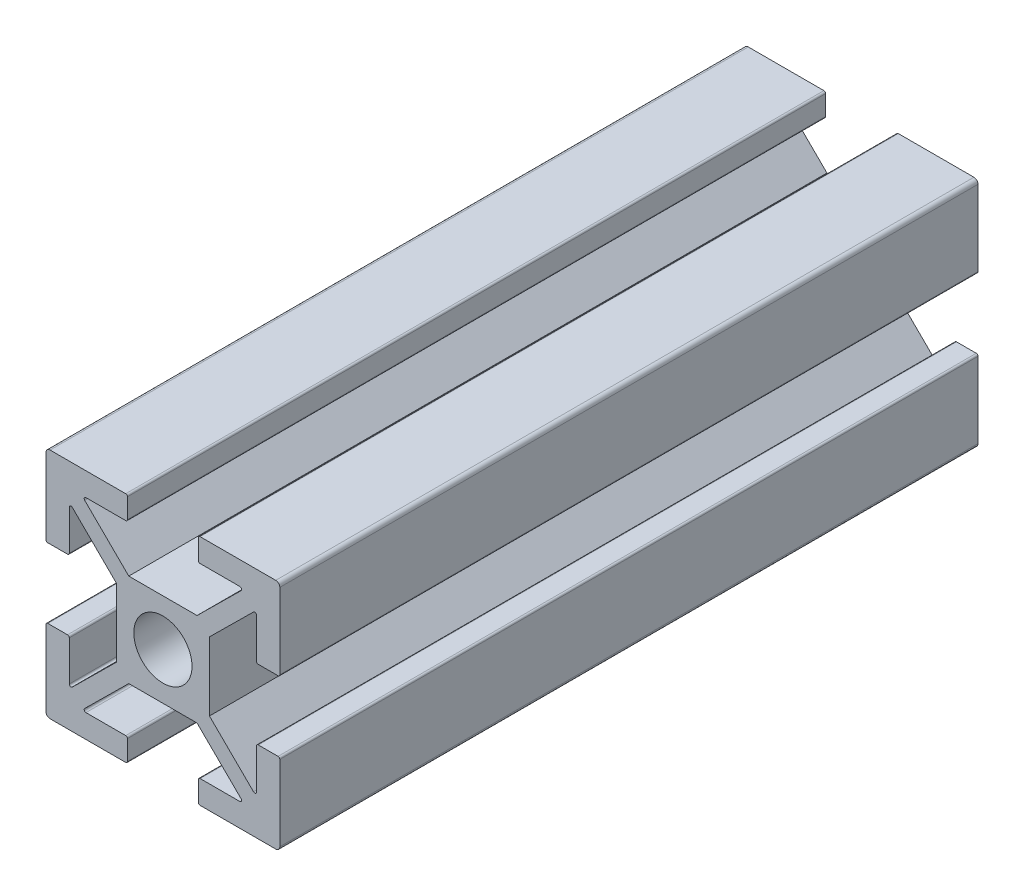
SolidWorks part; units mm, degrees
ref_plane "Front Plane" through (0, 0, 0) normal (0, 0, 1) x (1, 0, 0)
ref_plane "Top Plane" through (0, 0, 0) normal (0, 1, 0) x (1, 0, 0)
ref_plane "Right Plane" through (0, 0, 0) normal (1, 0, 0) x (0, 0, -1)
sketch "Sketch1" plane through (0, 0, 0) normal (0, 0, 1) x (1, 0, 0)
  line L0 (-31.3764, -0.0618) -> (-29.6764, -0.0618)
  line L1 (-24.6764, 6.9382) -> (-31.1764, 6.9382)
  line L2 (-31.5264, 0.0882) -> (-31.5264, 6.5882)
  line L3 (-18.5469, 0.9382) -> (-24.4133, 0.9382)
  line L4 (-25.4801, -6.0072) -> (-25.4801, -0.1164)
  line L5 (-29.5264, 0.0882) -> (-29.5264, 3.5244)
  line L6 (-28.0945, 4.9382) -> (-24.6764, 4.9382)
  line L7 (-24.5264, 5.0882) -> (-24.5264, 6.7882)
  line L8 (-29.5264, 4.9382) -> (-25.4801, 0.9382) construction
  line L9 (-29.271, 3.631) -> (-25.4801, -0.1164)
  line L10 (-28.1999, 4.6815) -> (-24.4133, 0.9382)
  line L11 (-13.4338, 4.9382) -> (-17.4801, 0.9382) construction
  line L12 (-21.4801, -3.0618) -> (-21.4801, 8.6268) construction
  line L13 (-21.4801, -3.0618) -> (-36.4642, -3.0618) construction
  line L14 (-14.7603, 4.6815) -> (-18.5469, 0.9382)
  line L15 (-13.6893, 3.631) -> (-17.4801, -0.1164)
  line L16 (-18.4338, 5.0882) -> (-18.4338, 6.7882)
  line L17 (-14.8657, 4.9382) -> (-18.2838, 4.9382)
  line L18 (-13.4338, 0.0882) -> (-13.4338, 3.5244)
  line L19 (-17.4801, -6.0072) -> (-17.4801, -0.1164)
  line L20 (-11.4338, 0.0882) -> (-11.4338, 6.5882)
  line L21 (-18.2838, 6.9382) -> (-11.7838, 6.9382)
  line L22 (-11.5838, -0.0618) -> (-13.2838, -0.0618)
  line L23 (-13.4338, -11.0618) -> (-17.4801, -7.0618) construction
  line L24 (-29.5264, -11.0618) -> (-25.4801, -7.0618) construction
  line L25 (-11.5838, -6.0618) -> (-13.2838, -6.0618)
  line L26 (-18.2838, -13.0618) -> (-11.7838, -13.0618)
  line L27 (-11.4338, -6.2118) -> (-11.4338, -12.7118)
  line L28 (-13.4338, -6.2118) -> (-13.4338, -9.648)
  line L29 (-14.8657, -11.0618) -> (-18.2838, -11.0618)
  line L30 (-18.4338, -11.2118) -> (-18.4338, -12.9118)
  line L31 (-13.6893, -9.7547) -> (-17.4801, -6.0072)
  line L32 (-14.7603, -10.8051) -> (-18.5469, -7.0618)
  line L33 (-28.1999, -10.8051) -> (-24.4133, -7.0618)
  line L34 (-29.271, -9.7547) -> (-25.4801, -6.0072)
  line L35 (-24.5264, -11.2118) -> (-24.5264, -12.9118)
  line L36 (-28.0945, -11.0618) -> (-24.6764, -11.0618)
  line L37 (-29.5264, -6.2118) -> (-29.5264, -9.648)
  line L38 (-18.5469, -7.0618) -> (-24.4133, -7.0618)
  line L39 (-31.5264, -6.2118) -> (-31.5264, -12.7118)
  line L40 (-24.6764, -13.0618) -> (-31.1764, -13.0618)
  line L41 (-31.3764, -6.0618) -> (-29.6764, -6.0618)
  circle A0 centre (-21.4801, -3.0618) radius 2.5
  arc A1 (-31.5264, 6.5882) -> (-31.1764, 6.9382) centre (-31.1764, 6.5882) cw
  arc A2 (-31.3764, -0.0618) -> (-31.5264, 0.0882) centre (-31.3764, 0.0882) cw
  arc A3 (-29.6764, -0.0618) -> (-29.5264, 0.0882) centre (-29.6764, 0.0882) ccw
  arc A4 (-24.6764, 6.9382) -> (-24.5264, 6.7882) centre (-24.6764, 6.7882) cw
  arc A5 (-24.6764, 4.9382) -> (-24.5264, 5.0882) centre (-24.6764, 5.0882) ccw
  arc A6 (-28.1999, 4.6815) -> (-28.0945, 4.9382) centre (-28.0945, 4.7882) cw
  arc A7 (-29.271, 3.631) -> (-29.5264, 3.5244) centre (-29.3764, 3.5244) ccw
  arc A8 (-13.6893, 3.631) -> (-13.4338, 3.5244) centre (-13.5838, 3.5244) cw
  arc A9 (-14.7603, 4.6815) -> (-14.8657, 4.9382) centre (-14.8657, 4.7882) ccw
  arc A10 (-18.2838, 4.9382) -> (-18.4338, 5.0882) centre (-18.2838, 5.0882) cw
  arc A11 (-18.2838, 6.9382) -> (-18.4338, 6.7882) centre (-18.2838, 6.7882) ccw
  arc A12 (-13.2838, -0.0618) -> (-13.4338, 0.0882) centre (-13.2838, 0.0882) cw
  arc A13 (-11.5838, -0.0618) -> (-11.4338, 0.0882) centre (-11.5838, 0.0882) ccw
  arc A14 (-11.4338, 6.5882) -> (-11.7838, 6.9382) centre (-11.7838, 6.5882) ccw
  arc A15 (-11.4338, -12.7118) -> (-11.7838, -13.0618) centre (-11.7838, -12.7118) cw
  arc A16 (-11.5838, -6.0618) -> (-11.4338, -6.2118) centre (-11.5838, -6.2118) cw
  arc A17 (-13.2838, -6.0618) -> (-13.4338, -6.2118) centre (-13.2838, -6.2118) ccw
  arc A18 (-18.2838, -13.0618) -> (-18.4338, -12.9118) centre (-18.2838, -12.9118) cw
  arc A19 (-18.2838, -11.0618) -> (-18.4338, -11.2118) centre (-18.2838, -11.2118) ccw
  arc A20 (-14.7603, -10.8051) -> (-14.8657, -11.0618) centre (-14.8657, -10.9118) cw
  arc A21 (-13.6893, -9.7547) -> (-13.4338, -9.648) centre (-13.5838, -9.648) ccw
  arc A22 (-29.271, -9.7547) -> (-29.5264, -9.648) centre (-29.3764, -9.648) cw
  arc A23 (-28.1999, -10.8051) -> (-28.0945, -11.0618) centre (-28.0945, -10.9118) ccw
  arc A24 (-24.6764, -11.0618) -> (-24.5264, -11.2118) centre (-24.6764, -11.2118) cw
  arc A25 (-24.6764, -13.0618) -> (-24.5264, -12.9118) centre (-24.6764, -12.9118) ccw
  arc A26 (-29.6764, -6.0618) -> (-29.5264, -6.2118) centre (-29.6764, -6.2118) cw
  arc A27 (-31.3764, -6.0618) -> (-31.5264, -6.2118) centre (-31.3764, -6.2118) ccw
  arc A28 (-31.5264, -12.7118) -> (-31.1764, -13.0618) centre (-31.1764, -12.7118) ccw
  point P27 (-18.4338, 4.9382)
  point P28 (-11.4338, -13.0618)
  point P47 (-17.4801, -3.0618)
  point P57 (-21.4801, 0.9382)
  point P59 (-18.4338, 6.9382)
  point P60 (-13.4338, -0.0618)
  point P61 (-11.4338, -0.0618)
  point P62 (-11.4338, 6.9382)
  point P112 (-25.4801, -3.0618)
  point P113 (-11.4338, -6.0618)
  point P114 (-13.4338, -6.0618)
  point P115 (-18.4338, -13.0618)
  point P116 (-21.4801, -7.0618)
  point P117 (-24.5264, -11.0618)
  point P118 (-24.5264, -13.0618)
  point P119 (-29.5264, -6.0618)
  point P120 (-18.4338, -11.0618)
  point P121 (-31.5264, -6.0618)
  point P122 (-31.5264, -13.0618)
  dimension "D3" = 0.35
  dimension "D4" = 0.15
  dimension "D5" = 0.15
  dimension "D6" = 0.15
  dimension "D7" = 0.15
  dimension "D8" = 0.15
  dimension "D9" = 0.15
  dimension "D1" = 0.75
  dimension "D2" = 0.75
extrude "Boss-Extrude1" add sketch "Sketch1" along normal blind 60
